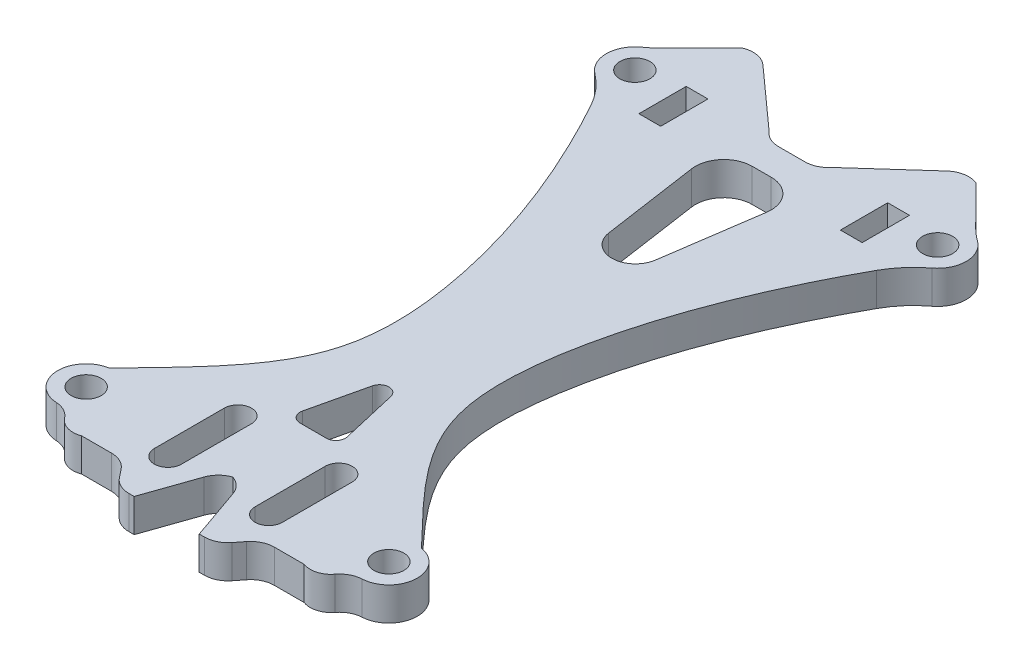
SolidWorks part; units mm, degrees
ref_plane "Alzado" through (0, 0, 0) normal (0, 0, 1) x (1, 0, 0)
ref_plane "Planta" through (0, 0, 0) normal (0, 1, 0) x (1, 0, 0)
ref_plane "Vista lateral" through (0, 0, 0) normal (1, 0, 0) x (0, 0, -1)
sketch "Croquis1" plane through (0, 0, 0) normal (0, 1, 0) x (1, 0, 0)
  line L0 (0.6064, -2.4342) -> (0.6064, -4.9347) construction
  line L1 (-15.8743, 31.8747) -> (-11.7541, 36.031)
  line L2 (17.087, 31.8747) -> (12.9668, 36.031)
  line L3 (-0.7819, 28.9238) -> (0.5656, 28.9238)
  line L4 (-6.0277, -35.3365) -> (-5.3469, -36.2017)
  line L5 (-3.3822, -37.1557) -> (-2.8348, -37.1557)
  line L6 (-2.8348, -37.1557) -> (-0.9275, -31.6963)
  line L7 (-4.7225, -24.3019) -> (-4.7225, -31.6963) construction
  line L8 (-3.2875, -24.3019) -> (-3.2875, -31.6963)
  line L9 (4.0476, -37.1557) -> (2.1402, -31.6963)
  line L10 (4.5949, -37.1557) -> (4.0476, -37.1557)
  line L11 (7.2405, -35.3365) -> (6.5596, -36.2017)
  line L12 (12.3646, -34.3825) -> (9.2051, -34.3825)
  line L13 (-0.7874, -21.6656) -> (2.0002, -21.6656)
  line L14 (1.9946, 28.9238) -> (0.6471, 28.9238)
  line L15 (3.9289, 29.8398) -> (10.3273, 35.5864)
  line L16 (-2.7161, 29.8398) -> (-9.1146, 35.5864)
  line L17 (0.5656, 28.9238) -> (0.6471, 28.9238)
  line L18 (-6.1575, -24.3019) -> (-6.1575, -31.6963)
  line L19 (-6.2301, 18.1586) -> (-6.2301, 13.6614) construction
  line L20 (-4.7308, 18.1586) -> (-4.7308, 13.6614)
  line L22 (5.9352, -24.3019) -> (5.9352, -31.6963) construction
  line L23 (4.5002, -24.3019) -> (4.5002, -31.6963)
  line L24 (7.3703, -24.3019) -> (7.3703, -31.6963)
  line L25 (7.4429, 18.1586) -> (7.4429, 13.6614) construction
  line L26 (5.9435, 18.1586) -> (5.9435, 13.6614)
  line L28 (-0.3677, -14.4393) -> (-1.7615, -20.4393)
  line L29 (1.5804, -14.4393) -> (2.9743, -20.4393)
  line L30 (-0.3954, 25.733) -> (1.6082, 25.733)
  line L31 (4.5768, 22.3002) -> (3.0802, 12.0345)
  line L32 (-3.3641, 22.3002) -> (-1.8675, 12.0345)
  line L33 (-11.1518, -34.3825) -> (-7.9924, -34.3825)
  line L34 (-11.1936, 29.5554) -> (-8.8936, 29.5554)
  line L35 (-11.1936, 29.5554) -> (-11.1936, 24.5554)
  line L36 (-11.1936, 24.5554) -> (-8.8936, 24.5554)
  line L37 (-8.8936, 29.5554) -> (-8.8936, 24.5554)
  line L38 (12.4064, 29.5554) -> (10.1064, 29.5554)
  line L39 (12.4064, 29.5554) -> (12.4064, 24.5554)
  line L40 (10.1064, 29.5554) -> (10.1064, 24.5554)
  line L41 (12.4064, 24.5554) -> (10.1064, 24.5554)
  arc A0 (-2.7161, 29.8398) -> (-0.7819, 28.9238) centre (-0.7819, 31.4238) ccw
  arc A1 (0.6064, -30.1614) -> (-0.9275, -31.6963) centre (1.4326, -32.5209) ccw
  arc A2 (-3.3822, -37.1557) -> (-5.3469, -36.2017) centre (-3.3822, -34.6557) cw
  arc A3 (12.3646, -34.3825) -> (14.9036, -33.6487) centre (13.1407, -32.3083) ccw
  arc A4 (7.2405, -35.3365) -> (9.2051, -34.3825) centre (9.2051, -36.8825) cw
  arc A5 (4.5949, -37.1557) -> (6.5596, -36.2017) centre (4.5949, -34.6557) ccw
  arc A6 (0.6064, -30.1614) -> (2.1402, -31.6963) centre (-0.2199, -32.5209) cw
  arc A7 (3.9289, 29.8398) -> (1.9946, 28.9238) centre (1.9946, 31.4238) cw
  arc A8 (-3.2875, -24.3019) -> (-6.1575, -24.3019) centre (-4.7225, -24.3019) ccw
  arc A9 (-6.1575, -31.6963) -> (-3.2875, -31.6963) centre (-4.7225, -31.6963) ccw
  arc A10 (-4.7308, 18.1586) -> (-7.7295, 18.1586) centre (-6.2301, 18.1586) ccw
  arc A11 (-7.7295, 13.6614) -> (-4.7308, 13.6614) centre (-6.2301, 13.6614) ccw
  arc A12 (4.5002, -24.3019) -> (7.3703, -24.3019) centre (5.9352, -24.3019) cw
  arc A13 (7.3703, -31.6963) -> (4.5002, -31.6963) centre (5.9352, -31.6963) cw
  arc A14 (5.9435, 18.1586) -> (8.9422, 18.1586) centre (7.4429, 18.1586) cw
  arc A15 (8.9422, 13.6614) -> (5.9435, 13.6614) centre (7.4429, 13.6614) cw
  arc A16 (1.5804, -14.4393) -> (-0.3677, -14.4393) centre (0.6064, -14.6656) ccw
  arc A17 (2.0002, -21.6656) -> (2.9743, -20.4393) centre (2.0002, -20.6656) ccw
  arc A18 (-1.7615, -20.4393) -> (-0.7874, -21.6656) centre (-0.7874, -20.6656) ccw
  arc A19 (1.6082, 25.733) -> (4.5768, 22.3002) centre (1.6082, 22.733) cw
  arc A20 (-0.3954, 25.733) -> (-3.3641, 22.3002) centre (-0.3954, 22.733) ccw
  arc A21 (3.0802, 12.0345) -> (-1.8675, 12.0345) centre (0.6064, 12.3952) cw
  arc A22 (-9.1146, 35.5864) -> (-11.7541, 36.031) centre (-10.7851, 33.7264) ccw
  arc A23 (10.3273, 35.5864) -> (12.9668, 36.031) centre (11.9978, 33.7264) cw
  circle A24 centre (16.6064, -29.6694) radius 1.5875
  arc A25 (14.9036, -33.6487) -> (16.763, -32.6653) centre (16.8936, -35.1619) cw
  arc A26 (17.0864, -26.7081) -> (16.763, -32.6653) centre (16.6064, -29.6694) cw
  circle A27 centre (-15.3936, 28.3306) radius 1.5875
  circle A28 centre (16.6064, 28.3306) radius 1.5875
  arc A29 (18.4275, 25.9215) -> (18.3651, 30.7856) centre (16.6064, 28.3306) ccw
  arc A30 (-17.2148, 25.9215) -> (-17.1524, 30.7856) centre (-15.3936, 28.3306) cw
  arc A31 (18.3651, 30.7856) -> (17.087, 31.8747) centre (24.1889, 38.9148) cw
  arc A32 (-17.1524, 30.7856) -> (-15.8743, 31.8747) centre (-22.9761, 38.9148) ccw
  arc A33 (-14.4939, 22.7834) -> (-17.2148, 25.9215) centre (-23.2452, 17.9444) ccw
  arc A34 (15.7067, 22.7834) -> (18.4275, 25.9215) centre (24.4579, 17.9444) cw
  circle A35 centre (-15.3936, -29.6694) radius 1.5875
  arc A36 (-6.0277, -35.3365) -> (-7.9924, -34.3825) centre (-7.9924, -36.8825) ccw
  arc A37 (-11.1518, -34.3825) -> (-13.6908, -33.6487) centre (-11.9279, -32.3083) cw
  arc A38 (-15.8736, -26.7081) -> (-15.5503, -32.6653) centre (-15.3936, -29.6694) ccw
  arc A39 (-13.6908, -33.6487) -> (-15.5503, -32.6653) centre (-15.6809, -35.1619) ccw
  spline S0 degree 3 poles (17.0864, -26.7081) (12.0101, -21.42) (5.2527, -14.7242) (6.9401, 4.5894) (12.2424, 16.5183) (15.7067, 22.7834) knots 0 0 0 0 0.308743 0.525126 0.939196 0.939196 0.939196 0.939196
  spline S1 degree 3 poles (-15.8736, -26.7081) (-10.7973, -21.42) (-4.0399, -14.7242) (-5.7273, 4.5894) (-11.0297, 16.5183) (-14.4939, 22.7834) knots 0 0 0 0 0.308743 0.525126 0.939196 0.939196 0.939196 0.939196
  point P12 (-4.7225, -27.9991)
  point P24 (-11.4436, 27.0307)
  point P48 (-6.2301, 15.91)
  point P86 (5.9352, -27.9991)
  point P93 (7.4429, 15.91)
  point P107 (3.2591, -21.6656)
  point P110 (-2.0464, -21.6656)
  dimension "D1" = 2.5
  dimension "D2" = 2.5
  dimension "D3" = 1
  dimension "D5" = 3
  dimension "D6" = 2.5
  dimension "D7" = 2.5
  dimension "D8" = 3.175
  dimension "D13" = 10
  dimension "D14" = 10
  dimension "D15" = 10
  dimension "D16" = 2.5
  dimension "D17" = 2.5
  dimension "D4" = 6
  dimension "D9" = 16
  dimension "D10" = 2.3
  dimension "D11" = 5
  dimension "D12" = 9.5
extrude "Saliente-Extruir1" add sketch "Croquis1" along normal blind 3.5
